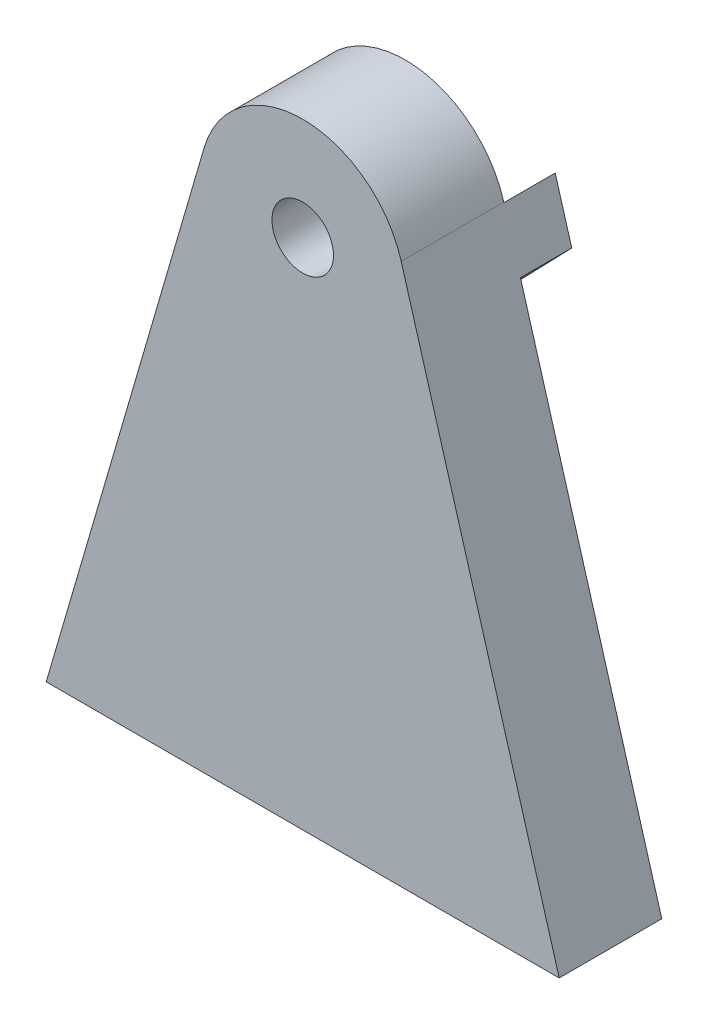
SolidWorks part; units mm, degrees
ref_plane "Front" through (0, 0, 0) normal (0, 0, 1) x (1, 0, 0)
ref_plane "Top" through (0, 0, 0) normal (0, 1, 0) x (1, 0, 0)
ref_plane "Right" through (0, 0, 0) normal (1, 0, 0) x (0, 0, -1)
sketch "Sketch1" plane through (0, 0, 0) normal (0, 0, 1) x (1, 0, 0)
  line L0 (-8.7884, 13.4112) -> (-12.7, 0)
  line L1 (-12.7, 0) -> (0, 0)
  line L2 (0, 0) -> (-3.9116, 13.4112)
  arc A0 (-3.9116, 13.4112) -> (-8.7884, 13.4112) centre (-6.35, 12.7) ccw
  point P7 (-6.35, 0)
  dimension "D1" = 12.7
  dimension "D2" = 2.54
  dimension "D3" = 12.7
extrude "Boss-Extrude1" add sketch "Sketch1" along normal blind 2.54
sketch "Sketch3" plane through (0, 0, 2.54) normal (0, 0, 1) x (1, 0, 0)
  circle A0 centre (-6.35, 12.7) radius 0.762
  dimension "D1" = 1.524
sketch "Sketch4" plane through (0, 0, 2.54) normal (0, 0, 1) x (1, 0, 0)
  line L0 (-12.7, 0) -> (0, 0) construction
  line L1 (-6.3187, 10.9042) -> (-2.7898, 14.5585) construction
  line L2 (-6.3187, 10.9042) -> (-8.1458, 12.6687) construction
  line L3 (-8.1458, 12.6687) -> (-4.6169, 16.3229) construction
  line L4 (-2.7898, 14.5585) -> (-4.6169, 16.3229) construction
  point P4 (-6.35, 12.7)
  dimension "D1" = 2.54
  dimension "D2" = 1.27
  dimension "D3" = 1.27
  dimension "D4" = 5.08
  dimension "D5" = 46
sketch "Sketch5" plane through (0, 0, 2.54) normal (0, 0, 1) x (1, 0, 0)
  line L0 (-6.3187, 10.9042) -> (-2.7898, 14.5585) construction
  line L1 (-6.3187, 10.9042) -> (-3.9084, 13.4001)
  line L2 (-6.3187, 10.9042) -> (-5.4051, 10.022)
  line L3 (-5.4051, 10.022) -> (-3.4988, 11.996)
  line L4 (-3.9084, 13.4001) -> (-3.4988, 11.996)
  line L6 (-6.3187, 10.9042) -> (-8.1458, 12.6687) construction
  line L7 (0, 0) -> (-3.9116, 13.4112) construction
  dimension "D1" = 1.27
extrude "Boss-Extrude2" add sketch "Sketch5" against normal blind 3.81
extrude "Cut-Extrude1" cut sketch "Sketch3" against normal blind 2.54
